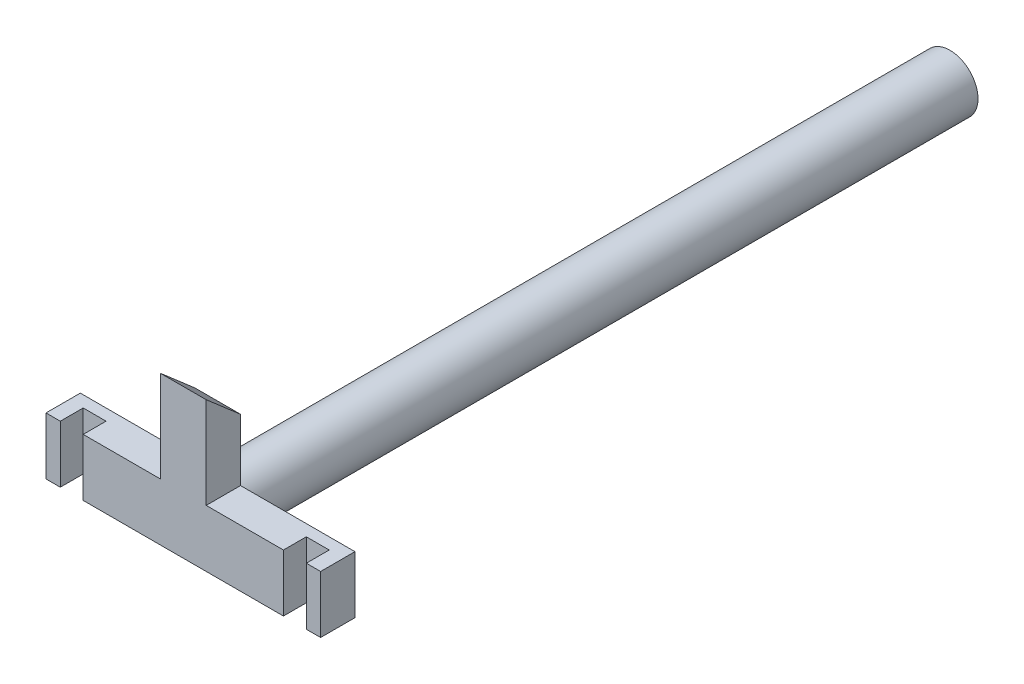
SolidWorks part; units mm, degrees
ref_plane "Front Plane" through (0, 0, 0) normal (0, 0, 1) x (1, 0, 0)
ref_plane "Top Plane" through (0, 0, 0) normal (0, 1, 0) x (1, 0, 0)
ref_plane "Right Plane" through (0, 0, 0) normal (1, 0, 0) x (0, 0, -1)
sketch "Sketch1" plane through (0, 0, 0) normal (0, 0, 1) x (1, 0, 0)
  circle A0 centre (0, 0) radius 2.45
  dimension "D1" = 4.9
extrude "Boss-Extrude1" add sketch "Sketch1" along normal blind 64
sketch "Sketch2" plane through (0, 0, 64) normal (0, 0, 1) x (1, 0, 0)
  line L1 (-12, 2.5) -> (12, 2.5)
  line L2 (-12, 2.5) -> (-12, -2.5)
  line L3 (-12, -2.5) -> (12, -2.5)
  line L4 (12, 2.5) -> (12, -2.5)
  line L5 (-12, 2.5) -> (12, -2.5) construction
  line L6 (-12, -2.5) -> (12, 2.5) construction
  point P0 (0, 0)
  dimension "D1" = 5
  dimension "D2" = 24
extrude "Boss-Extrude2" add sketch "Sketch2" along normal blind 3
sketch "Sketch3" plane through (0, 0, 67) normal (0, 0, 1) x (1, 0, 0)
  line L0 (12, 2.5) -> (-12, 2.5) construction
  line L1 (8.75, 2.5) -> (10.75, 2.5)
  line L2 (8.75, 2.5) -> (8.75, -2.5)
  line L3 (8.75, -2.5) -> (10.75, -2.5)
  line L4 (10.75, 2.5) -> (10.75, -2.5)
  line L5 (8.75, 2.5) -> (10.75, -2.5) construction
  line L6 (8.75, -2.5) -> (10.75, 2.5) construction
  line L7 (-12, -2.5) -> (12, -2.5) construction
  line L8 (12, -2.5) -> (12, 2.5) construction
  line L9 (0, 2.5) -> (0, -2.5) construction
  line L10 (-8.75, -2.5) -> (-10.75, 2.5) construction
  line L11 (-8.75, 2.5) -> (-10.75, -2.5) construction
  line L12 (-10.75, 2.5) -> (-10.75, -2.5)
  line L13 (-8.75, -2.5) -> (-10.75, -2.5)
  line L14 (-8.75, 2.5) -> (-8.75, -2.5)
  line L15 (-8.75, 2.5) -> (-10.75, 2.5)
  point P0 (9.75, 0)
  point P17 (-9.75, 0)
  dimension "D1" = 1.25
  dimension "D2" = 2
extrude "Cut-Extrude2" cut sketch "Sketch3" against normal blind 2
sketch "Sketch4" plane through (0, 0, 67) normal (0, 0, 1) x (1, 0, 0)
  line L0 (8.75, 2.5) -> (-8.75, 2.5) construction
  line L1 (-2, 10.5) -> (2, 10.5)
  line L2 (-2, 10.5) -> (-2, 2.5)
  line L3 (-2, 2.5) -> (2, 2.5)
  line L4 (2, 10.5) -> (2, 2.5)
  line L5 (-2, 10.5) -> (2, 2.5) construction
  line L6 (-2, 2.5) -> (2, 10.5) construction
  point P0 (0, 6.5)
  point P7 (0, 0)
  dimension "D1" = 8
  dimension "D2" = 4
extrude "Boss-Extrude3" add sketch "Sketch4" against normal up to surface (3 mm away) up to face at (2.45, 0, 64)
sketch "Sketch5" plane through (2, 0, 0) normal (1, 0, 0) x (0, 0, -1)
  line L0 (-67, 10.5) -> (-64, 7.9)
  line L1 (-64, 10.5) -> (-64, 2.5) construction
  line L2 (-64, 7.9) -> (-64, 10.5)
  line L3 (-64, 10.5) -> (-67, 10.5)
  dimension "D1" = 2.6
extrude "Cut-Extrude3" cut sketch "Sketch5" against normal up to next
